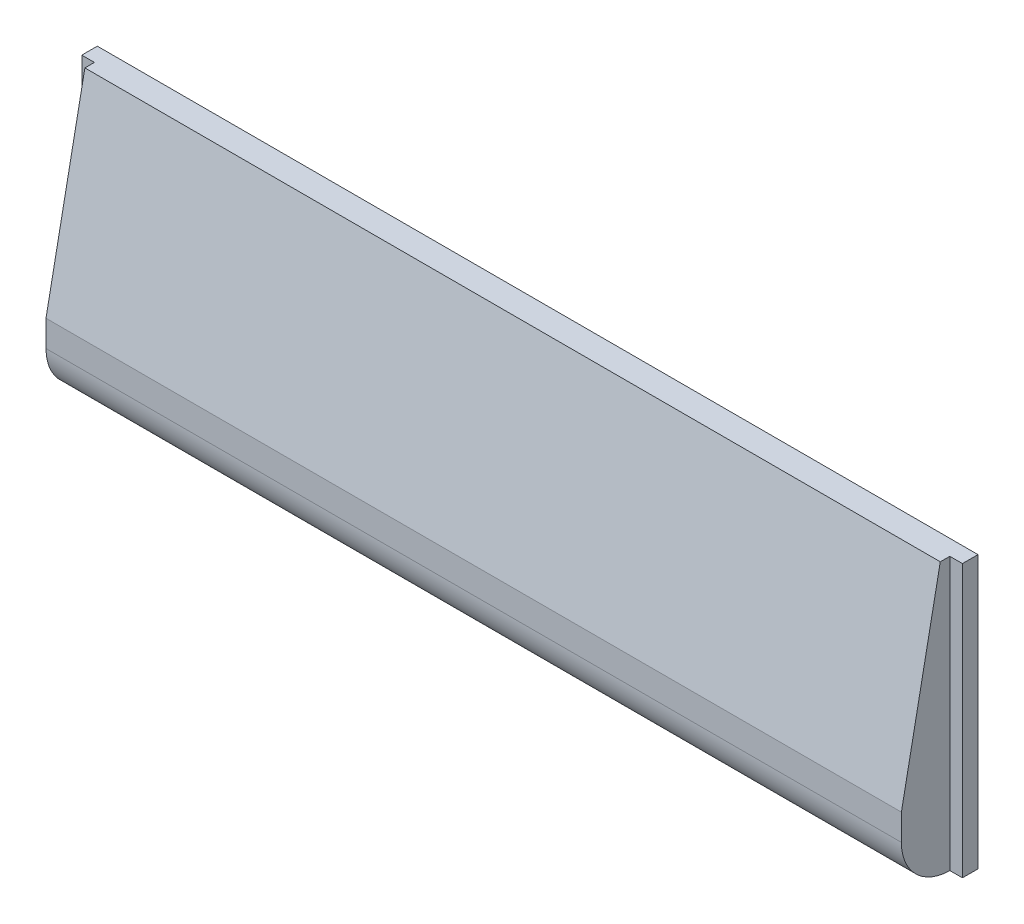
SolidWorks part; units mm, degrees
ref_plane "Plan de face" through (0, 0, 0) normal (0, 0, 1) x (1, 0, 0)
ref_plane "Plan de dessus" through (0, 0, 0) normal (0, 1, 0) x (1, 0, 0)
ref_plane "Plan de droite" through (0, 0, 0) normal (1, 0, 0) x (0, 0, -1)
sketch "Esquisse1" plane through (0, 0, 0) normal (0, 0, 1) x (1, 0, 0)
  line L1 (-22.65, -7) -> (22.65, -7)
  line L2 (-22.65, -7) -> (-22.65, 7)
  line L3 (-22.65, 7) -> (22.65, 7)
  line L4 (22.65, -7) -> (22.65, 7)
  line L5 (-22.65, -7) -> (22.65, 7) construction
  line L6 (-22.65, 7) -> (22.65, -7) construction
  point P0 (0, 0)
  dimension "D1" = 45.3
  dimension "D2" = 14
extrude "Boss.-Extru.1" add sketch "Esquisse1" along normal blind 0.8
sketch "Esquisse2" plane through (0, 0, 0.8) normal (0, 0, 1) x (1, 0, 0)
  line L0 (22.65, 7) -> (-22.65, 7) construction
  line L1 (-22, -7) -> (22, -7)
  line L2 (-22, -7) -> (-22, 7)
  line L3 (-22, 7) -> (22, 7)
  line L4 (22, -7) -> (22, 7)
  line L5 (-22, -7) -> (22, 7) construction
  line L6 (-22, 7) -> (22, -7) construction
  point P0 (0, 0)
  dimension "D1" = 44
extrude "Boss.-Extru.2" add sketch "Esquisse2" along normal blind 5
sketch "Esquisse4" plane through (-22, 0, 0) normal (-1, 0, 0) x (0, 0, 1)
  line L0 (0.8, 7) -> (1.29, 7)
  line L1 (5.8, 7) -> (0.8, 7) construction
  line L2 (3.29, -10.1923) -> (3.29, 11.781)
  line L3 (0.8, 7) -> (0.8, -7) construction
  line L4 (1.29, 7) -> (3.29, -3.15)
  line L5 (3.29, -3.15) -> (3.29, -4.5)
  line L6 (5.8, -7) -> (0.8, -7) construction
  line L7 (1.29, 7) -> (7.4974, 9.5955)
  line L8 (7.4974, 9.5955) -> (9.6335, -10.6768)
  line L9 (9.6335, -10.6768) -> (0.8, -7)
  arc A0 (3.29, -4.5) -> (0.8, -7) centre (0.79, -4.5) cw
  dimension "D1" = 0.49
  dimension "D2" = 2.49
  dimension "D3" = 10.15
  dimension "D4" = 1.35
extrude "Enlèv. mat.-Extru.1" cut sketch "Esquisse4" against normal blind 57 contours L7 L8 L9 A0 L5 L4
